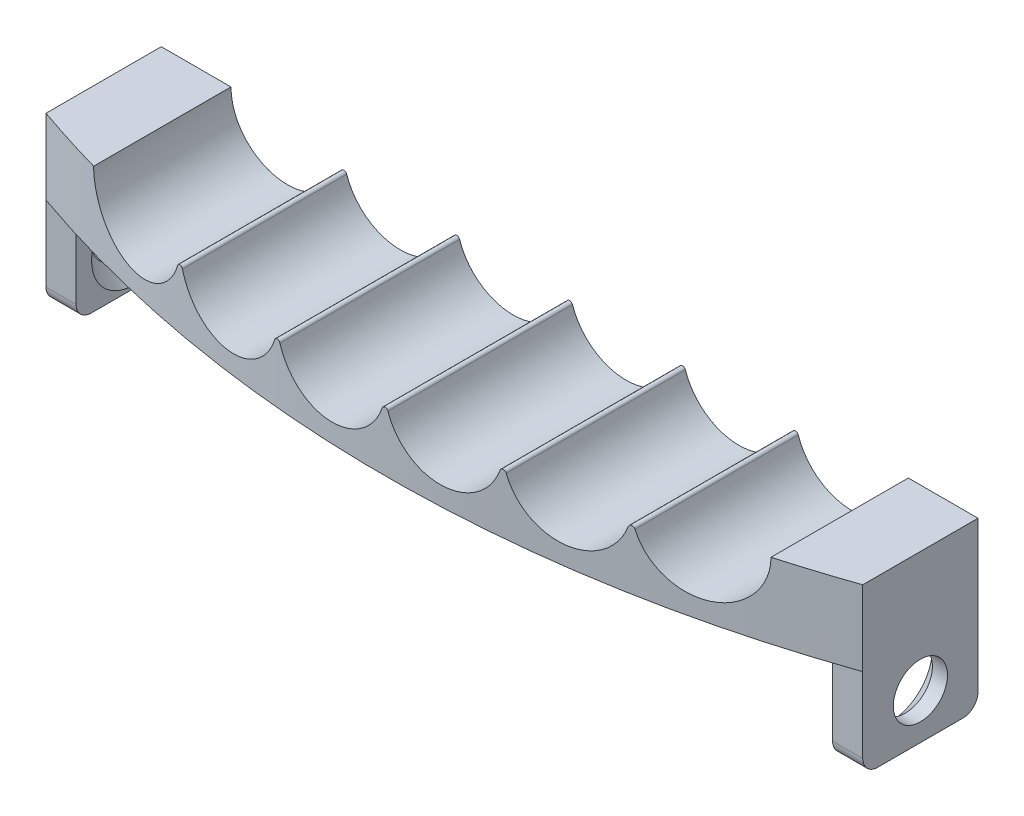
SolidWorks part; units mm, degrees
ref_plane "Plano frontal" through (0, 0, 0) normal (0, 0, 1) x (1, 0, 0)
ref_plane "Plano superior" through (0, 0, 0) normal (0, 1, 0) x (1, 0, 0)
ref_plane "Plano direito" through (0, 0, 0) normal (1, 0, 0) x (0, 0, -1)
sketch "Esboço2" plane through (0, 0, 0) normal (0, 0, 1) x (1, 0, 0)
  line L0 (-22.5, 0) -> (22.5, 0) construction
  line L1 (-22.5, 0) -> (-27.13, 0)
  line L2 (-27.13, 0) -> (-27.13, -5)
  line L3 (-27.13, -5) -> (27.13, -5)
  line L4 (27.13, -5) -> (27.13, 0)
  line L5 (27.13, 0) -> (22.5, 0)
  arc A0 (-22.5, 0) -> (-15, 0) centre (-18.75, 0) ccw
  arc A1 (-15, 0) -> (-7.5, 0) centre (-11.25, 0) ccw
  arc A2 (-7.5, 0) -> (0, 0) centre (-3.75, 0) ccw
  arc A3 (0, 0) -> (7.5, 0) centre (3.75, 0) ccw
  arc A4 (7.5, 0) -> (15, 0) centre (11.25, 0) ccw
  arc A5 (15, 0) -> (22.5, 0) centre (18.75, 0) ccw
  point P15 (0, -5)
  point P20 (5.268, 0)
  dimension "D1" = 7.5
  dimension "D3" = 4.63
  dimension "D4" = 5
  dimension "D2" = 6
extrude "Ressalto-extrusão2" add sketch "Esboço2" along normal blind 12.26
sketch "Esboço3" plane through (0, 0, 0) normal (0, 1, 0) x (1, 0, 0)
  line L0 (-27.13, -12.26) -> (27.13, -12.26) construction
  line L1 (-27.13, -7.6574) -> (-27.13, -12.26)
  line L2 (-27.13, -12.26) -> (-27.13, 0) construction
  line L3 (-27.13, -12.26) -> (27.13, -12.26)
  line L4 (27.13, -12.26) -> (27.13, -7.6574)
  line L5 (27.13, -12.26) -> (27.13, 0) construction
  arc A0 (-27.13, -7.6574) -> (27.13, -7.6574) centre (0, 70) ccw
  line M3 (-27.13, 0) -> (-27.13, -12.26)
  line M4 (-27.13, -12.26) -> (-22.5, -12.26)
  line M5 (-22.5, -12.26) -> (-22.5, 0)
  dimension "D1" = 164.52
extrude "Corte-extrusão1" cut sketch "Esboço3" against normal blind 12.26 contours A0 M3 M4 M5 | A0 L3 M5 | A0 L3 L4
fillet "Filete1" radius 0.2 5 edges at (15, 0, 5.4404) (7.5, 0, 5.9587) (0, 0, 6.13) (-7.5, 0, 5.9587) (-15, 0, 5.4404)
sketch "Esboço4" plane through (27.13, 0, 0) normal (1, 0, 0) x (0, 0, -1)
  line L0 (0, -5) -> (0, 0) construction
  line L1 (-7.6574, -5) -> (0, -5)
  line L2 (-7.6574, -5) -> (-7.6574, -11)
  line L3 (-7.6574, -11) -> (0, -11)
  line L4 (0, -5) -> (0, -11)
  circle A0 centre (-3.8287, -8) radius 1.8
  point P9 (0, 0)
  point P10 (-3.8287, -5)
  point P11 (0, 0)
  point P12 (0, -8)
  dimension "D2" = 3.6
  dimension "D1" = 6
extrude "Ressalto-extrusão3" add sketch "Esboço4" against normal blind 2
mirror "Espelhar1" about plane through (0, 0, 0) normal (1, 0, 0) of "Ressalto-extrusão3"
fillet "Filete2" radius 1 4 edges at (26.13, -11, 7.6574) (26.13, -11, 0) (-26.13, -11, 0) (-26.13, -11, 7.6574)
chamfer "Chanfro1" distance 1 angle 45 2 edges at (25.13, -8, 2.0287) (-25.13, -8, 2.0287)
